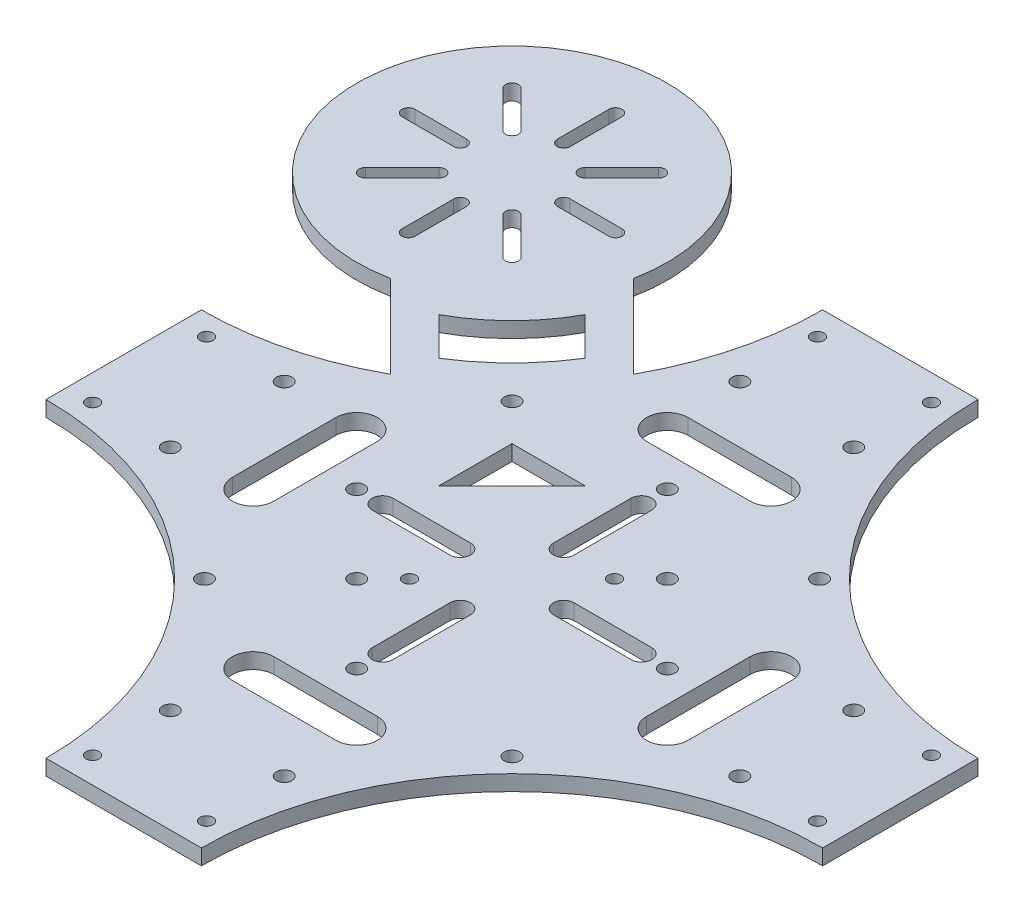
SolidWorks part; units mm, degrees
ref_plane "前视基准面" through (0, 0, 0) normal (0, 0, 1) x (1, 0, 0)
ref_plane "上视基准面" through (0, 0, 0) normal (0, 1, 0) x (1, 0, 0)
ref_plane "右视基准面" through (0, 0, 0) normal (1, 0, 0) x (0, 0, -1)
sketch "草图1" plane through (0, 0, 0) normal (0, 1, 0) x (1, 0, 0)
  line L0 (0, 0) -> (0, 75)
  line L1 (0, 0) -> (75, 0)
  line L2 (0, 0) -> (0, -75)
  line L3 (0, 0) -> (-75, 0)
  line L4 (0, 75) -> (15, 75)
  line L5 (0, 75) -> (-15, 75)
  line L6 (75, 0) -> (75, 15)
  line L7 (75, 0) -> (75, -15)
  line L8 (0, -75) -> (15, -75)
  line L9 (0, -75) -> (-15, -75)
  line L10 (-75, 0) -> (-75, -15)
  line L11 (-75, 0) -> (-75, 15)
  line L12 (75, 0) -> (70, 0)
  arc A0 (-75, 15) -> (-15, 75) centre (-75, 75) ccw
  arc A1 (15, 75) -> (75, 15) centre (75, 75) ccw
  arc A2 (75, -15) -> (15, -75) centre (75, -75) ccw
  arc A3 (-15, -75) -> (-75, -15) centre (-75, -75) ccw
  circle A4 centre (-11, 70) radius 1.25
  circle A5 centre (11, 70) radius 1.25
  circle A6 centre (70, -11) radius 1.25
  circle A7 centre (70, 11) radius 1.25
  circle A8 centre (-11, -70) radius 1.25
  circle A9 centre (11, -70) radius 1.25
  circle A10 centre (-70, 11) radius 1.25
  circle A11 centre (-70, -11) radius 1.25
  point P9 (0, 0)
  point P21 (0, 0)
  point P32 (0, 0)
  point P35 (0, 0)
  point P44 (0, 0)
  dimension "D1" = 4
extrude "凸台-拉伸1" add sketch "草图1" along normal blind 3 contours A2 L7 L1 L2 L8 A9 A6 | A3 L9 L2 L3 L10 A11 A8 | A0 L11 L3 L0 L5 A4 A10 | A1 L4 L0 L1 L6 A7 A5
sketch "草图2" plane through (0, 0, 0) normal (0, -1, 0) x (1, 0, 0)
  line L0 (0, 0) -> (-32.5736, -32.5736)
  line L1 (0, 0) -> (32.5736, -32.5736)
  line L2 (-31.4663, 0.3536) -> (-0.3536, 31.4663)
  line L3 (31.4663, -0.3536) -> (-0.3536, 31.4663)
  line L4 (0.3536, -31.4663) -> (31.4663, -0.3536)
  line L5 (0.3536, -31.4663) -> (-31.4663, 0.3536)
  arc A0 (-15, -75) -> (-75, -15) centre (-75, -75) ccw construction
  circle A2 centre (0.3536, -31.4663) radius 1.5
  circle A3 centre (31.4663, -0.3536) radius 1.5
  circle A4 centre (-0.3536, 31.4663) radius 1.5
  circle A5 centre (-31.4663, 0.3536) radius 1.5
  point P12 (-15.5563, -15.5563)
  point P16 (-15.9099, 15.9099)
  point P17 (15.9099, -15.9099)
extrude "切除-拉伸1" cut sketch "草图2" against normal blind 3 contours A3 | A2 | A5 | A4
sketch "草图3" plane through (0, 3, 0) normal (0, 1, 0) x (1, 0, 0)
  line L0 (0.3536, 31.4663) -> (-31.4663, -0.3536)
  line L1 (-15.5563, 15.5563) -> (-22.6274, 22.6274)
  line L2 (-15.5563, 15.5563) -> (-12.0208, 19.0919)
  line L3 (-15.5563, 15.5563) -> (-19.0919, 12.0208)
  line L4 (-19.0919, 12.0208) -> (-22.6274, 22.6274)
  line L5 (-12.0208, 19.0919) -> (-22.6274, 22.6274)
extrude "切除-拉伸2" cut sketch "草图3" against normal blind 3 contours L0 L5 L1 | L4 L0 L1
sketch "草图4" plane through (0, 3, 0) normal (0, 1, 0) x (1, 0, 0)
  line L0 (31.4663, 0.3536) -> (-0.3536, -31.4663)
  line L1 (0, 0) -> (21.2132, -21.2132)
  line L2 (28.2843, -14.1421) -> (14.1421, -28.2843)
  line L3 (14.1421, -28.2843) -> (28.2843, -14.1421) construction
  line L4 (8.4817, -22.6239) -> (22.6239, -8.4817)
  line L5 (19.8025, -33.9447) -> (33.9447, -19.8025)
  arc A0 (8.4817, -22.6239) -> (19.8025, -33.9447) centre (14.1421, -28.2843) ccw
  arc A1 (33.9447, -19.8025) -> (22.6239, -8.4817) centre (28.2843, -14.1421) ccw
  point P9 (21.2132, -21.2132)
extrude "切除-拉伸3" cut sketch "草图4" against normal blind 3
sketch "草图5" plane through (0, 3, 0) normal (0, 1, 0) x (1, 0, 0)
  line L0 (-12.0208, 19.0919) -> (-8.4853, 22.6274)
  line L1 (-8.4853, 22.6274) -> (-22.6274, 22.6274)
  line L2 (-19.0919, 12.0208) -> (-22.6274, 8.4853)
  line L3 (-22.6274, 8.4853) -> (-22.6274, 22.6274)
  line L4 (-12.0208, 19.0919) -> (-22.6274, 22.6274)
  line M28 (-19.0919, 12.0208) -> (-22.6274, 22.6274)
extrude "切除-拉伸4" cut sketch "草图5" against normal blind 10 contours L3 L2 M28 | L4 L0 L1
sketch "草图6" plane through (0, 3, 0) normal (0, 1, 0) x (1, 0, 0)
  line L0 (0, 0) -> (-28.2843, -28.2843)
  line L1 (-28.2843, -28.2843) -> (-35.3553, -21.2132)
  line L2 (0, 0) -> (-22.6274, 22.6274)
  circle A0 centre (-35.3553, -21.2132) radius 1.5
  circle A1 centre (-21.2132, -35.3553) radius 1.5
  circle A2 centre (35.3553, 21.2132) radius 1.5
  circle A3 centre (21.2132, 35.3553) radius 1.5
extrude "切除-拉伸5" cut sketch "草图6" against normal blind 10 contours A1 | A0 | A2 | A3
sketch "草图7" plane through (0, 3, 0) normal (0, 1, 0) x (1, 0, 0)
  circle A0 centre (-29.6985, 29.6985) radius 1.5
  circle A1 centre (29.6985, 29.6985) radius 1.5
  circle A2 centre (29.6985, -29.6985) radius 1.5
  circle A3 centre (-29.6985, -29.6985) radius 1.5
  point P11 (0, 0)
  dimension "D1" = 4
extrude "切除-拉伸8" cut sketch "草图7" against normal blind 10
sketch "草图8" plane through (0, 3, 0) normal (0, 1, 0) x (1, 0, 0)
  circle A0 centre (-11, 55) radius 1.5
  circle A1 centre (11, 55) radius 1.5
  circle A2 centre (55, 11) radius 1.5
  circle A3 centre (55, -11) radius 1.5
  circle A4 centre (11, -55) radius 1.5
  circle A5 centre (-11, -55) radius 1.5
  circle A6 centre (-55, -11) radius 1.5
  circle A7 centre (-55, 11) radius 1.5
  point P21 (0, 0)
  dimension "D1" = 4
extrude "切除-拉伸9" cut sketch "草图8" against normal blind 10
sketch "草图9" plane through (0, 3, 0) normal (0, 1, 0) x (1, 0, 0)
  circle A0 centre (0, 0) radius 15
extrude "切除-拉伸10" cut sketch "草图9" against normal blind 10
sketch "草图11" plane through (0, 3, 0) normal (0, 1, 0) x (1, 0, 0)
  circle A0 centre (-35.3553, -21.2132) radius 1.5
  circle A2 centre (35.3553, 21.2132) radius 1.5
  circle A3 centre (21.2132, 35.3553) radius 1.5
  circle A4 centre (0.3536, 31.4663) radius 1.5
  circle A5 centre (31.4663, 0.3536) radius 1.5
  circle A6 centre (-0.3536, -31.4663) radius 1.5
  circle A7 centre (-31.4663, -0.3536) radius 1.5
  circle A8 centre (-21.2132, -35.3553) radius 1.5
extrude "凸台-拉伸3" add sketch "草图11" against normal blind 3
sketch "草图12" plane through (0, 3, 0) normal (0, 1, 0) x (1, 0, 0)
  line L0 (0, 0) -> (-40, 0)
  line L1 (-40, 0) -> (-40, 10)
  line L2 (-40, 0) -> (-40, -10)
  line L3 (-40, -10) -> (-40, 10) construction
  line L4 (-44, -10) -> (-44, 10)
  line L5 (-36, -10) -> (-36, 10)
  line L6 (-10, 40) -> (10, 40) construction
  line L7 (-10, 44) -> (10, 44)
  line L8 (-10, 36) -> (10, 36)
  line L9 (40, 10) -> (40, -10) construction
  line L10 (44, 10) -> (44, -10)
  line L11 (36, 10) -> (36, -10)
  line L12 (10, -40) -> (-10, -40) construction
  line L13 (10, -44) -> (-10, -44)
  line L14 (10, -36) -> (-10, -36)
  arc A0 (-44, -10) -> (-36, -10) centre (-40, -10) ccw
  arc A1 (-36, 10) -> (-44, 10) centre (-40, 10) ccw
  arc A2 (-10, 44) -> (-10, 36) centre (-10, 40) ccw
  arc A3 (10, 36) -> (10, 44) centre (10, 40) ccw
  arc A4 (44, 10) -> (36, 10) centre (40, 10) ccw
  arc A5 (36, -10) -> (44, -10) centre (40, -10) ccw
  arc A6 (10, -44) -> (10, -36) centre (10, -40) ccw
  arc A7 (-10, -36) -> (-10, -44) centre (-10, -40) ccw
  point P3 (-40, 0)
  point P13 (0, 40)
  point P20 (40, 0)
  point P27 (0, -40)
  point P34 (0, 0)
  dimension "D1" = 4
extrude "切除-拉伸12" cut sketch "草图12" against normal blind 3
sketch "草图14" plane through (0, 3, 0) normal (0, 1, 0) x (1, 0, 0)
  line L0 (22.8277, -8.285) -> (8.285, -22.8277) construction
  line L1 (19.8025, -33.9447) -> (33.9447, -19.8025) construction
  line L2 (8.285, -22.8277) -> (22.8277, -8.285)
  line L3 (22.8277, -8.285) -> (19.8025, -33.9447)
  line L4 (19.8025, -33.9447) -> (33.9447, -19.8025)
  arc A0 (8.285, -22.8277) -> (19.8025, -33.9447) centre (14.1421, -28.2843) ccw
  arc A1 (8.285, -22.8277) -> (19.8025, -33.9447) centre (14.1421, -28.2843) ccw construction
  arc A2 (33.9447, -19.8025) -> (22.8277, -8.285) centre (28.2843, -14.1421) ccw construction
  arc A3 (22.8277, -8.285) -> (32.1857, -7.1522) centre (28.2843, -14.1421) ccw
  circle A4 centre (28.2843, -14.1421) radius 8.005
extrude "凸台-拉伸4" add sketch "草图14" against normal blind 3 contours A3 A4 L3 | L2 A3 L3 | A3 L2 A0 L3 | A3 L3 L4
sketch "草图15" plane through (0, 3, 0) normal (0, 1, 0) x (1, 0, 0)
  circle A0 centre (0, 0) radius 15
extrude "凸台-拉伸5" add sketch "草图15" against normal blind 3
sketch "草图17" plane through (0, 3, 0) normal (0, 1, 0) x (1, 0, 0)
  line L0 (0, 0) -> (0, -20)
  line L1 (0, -20) -> (0, -10) construction
  line L2 (-2, -20) -> (-2, -10)
  line L3 (2, -20) -> (2, -10)
  line L4 (-20, 0) -> (-10, 0) construction
  line L5 (-20, 2) -> (-10, 2)
  line L6 (-20, -2) -> (-10, -2)
  line L7 (0, 20) -> (0, 10) construction
  line L8 (2, 20) -> (2, 10)
  line L9 (-2, 20) -> (-2, 10)
  line L10 (20, 0) -> (10, 0) construction
  line L11 (20, -2) -> (10, -2)
  line L12 (20, 2) -> (10, 2)
  arc A0 (-2, -20) -> (2, -20) centre (0, -20) ccw
  arc A1 (2, -10) -> (-2, -10) centre (0, -10) ccw
  arc A2 (-20, 2) -> (-20, -2) centre (-20, 0) ccw
  arc A3 (-10, -2) -> (-10, 2) centre (-10, 0) ccw
  arc A4 (2, 20) -> (-2, 20) centre (0, 20) ccw
  arc A5 (-2, 10) -> (2, 10) centre (0, 10) ccw
  arc A6 (20, -2) -> (20, 2) centre (20, 0) ccw
  arc A7 (10, 2) -> (10, -2) centre (10, 0) ccw
  point P3 (0, -15)
  point P13 (-15, 0)
  point P20 (0, 15)
  point P27 (15, 0)
  point P33 (0, 0)
  dimension "D1" = 4
extrude "切除-拉伸13" cut sketch "草图17" against normal blind 3 contours L8 A5 L9 A4 | L12 A7 L11 A6 | L3 A1 L2 A0 | L5 A3 L6 A2
sketch "草图18" plane through (0, 3, 0) normal (0, 1, 0) x (1, 0, 0)
  line L0 (0, 0) -> (-32.5736, 32.5736)
  line L1 (-32.5736, 32.5736) -> (-46.7157, 46.7157)
  line L2 (-50.2513, 50.2513) -> (-61.9773, 38.5252)
  line L3 (-46.7157, 46.7157) -> (-50.2513, 50.2513)
  line L4 (-61.9773, 38.5252) -> (-38.5252, 61.9773)
  line L5 (-38.5252, 61.9773) -> (-22.5002, 45.9523)
  line L6 (-61.9773, 38.5252) -> (-45.9523, 22.5002)
  arc A0 (-75, 15) -> (-15, 75) centre (-75, 75) ccw construction
  circle A1 centre (-67.9289, 67.9289) radius 30
  circle A2 centre (-75, 75) radius 60
extrude "凸台-拉伸7" add sketch "草图18" against normal blind 3 contours L4 A1 L2 | L2 A1 L3 | L3 A1 L4 | L6 A2 L1 A1 | L1 A2 L5 A1
sketch "草图19" plane through (0, 3, 0) normal (0, 1, 0) x (1, 0, 0)
  line L0 (-61.9773, 38.5252) -> (-38.5252, 61.9773)
  line L1 (-50.2513, 50.2513) -> (-36.1091, 36.1091)
  line L2 (-36.1091, 36.1091) -> (-43.1802, 29.0381)
  line L3 (-36.1091, 36.1091) -> (-29.0381, 43.1802)
  line L4 (-29.0381, 43.1802) -> (-37.1408, 51.2829)
  line L5 (-37.1408, 51.2829) -> (-51.2829, 37.1408)
  line L6 (-51.2829, 37.1408) -> (-43.1802, 29.0381)
  circle A1 centre (-67.9289, 67.9289) radius 35
  circle A2 centre (-67.9289, 67.9289) radius 45
extrude "切除-拉伸14" cut sketch "草图19" against normal blind 3 contours L1 A2 L4 A1 | L6 A2 L1 A1
sketch "草图21" plane through (0, 3, 0) normal (0, 1, 0) x (1, 0, 0)
  line L0 (-61.9773, 38.5252) -> (-38.5252, 61.9773)
  line L1 (-67.9289, 67.9289) -> (-53.7868, 53.7868)
  line L2 (-82.0711, 82.0711) -> (-75, 75)
  line L3 (-67.9289, 67.9289) -> (-82.0711, 82.0711)
  line L4 (-53.7868, 53.7868) -> (-60.8579, 60.8579)
  line L5 (-82.0711, 82.0711) -> (-75, 75) construction
  line L6 (-81.1872, 82.955) -> (-74.1161, 75.8839)
  line L7 (-82.955, 81.1872) -> (-75.8839, 74.1161)
  line L8 (-60.8579, 60.8579) -> (-53.7868, 53.7868) construction
  line L9 (-59.974, 61.7417) -> (-52.9029, 54.6707)
  line L10 (-61.7417, 59.974) -> (-54.6707, 52.9029)
  arc A0 (-81.1872, 82.955) -> (-82.955, 81.1872) centre (-82.0711, 82.0711) ccw
  arc A1 (-75.8839, 74.1161) -> (-74.1161, 75.8839) centre (-75, 75) ccw
  arc A2 (-59.974, 61.7417) -> (-61.7417, 59.974) centre (-60.8579, 60.8579) ccw
  arc A3 (-54.6707, 52.9029) -> (-52.9029, 54.6707) centre (-53.7868, 53.7868) ccw
  point P2 (-78.5355, 78.5355)
  point P15 (-57.3223, 57.3223)
extrude "切除-拉伸15" cut sketch "草图21" against normal blind 3
pattern_circular "阵列(圆周)1" count 8 over 360 about axis through (-67.9289, 0, -67.9289) along (0, 1, 0) of "切除-拉伸15"
sketch "草图22" plane through (0, 3, 0) normal (0, 1, 0) x (1, 0, 0)
  line L0 (0, 0) -> (9.8995, 9.8995)
  line L1 (0, 0) -> (-9.8995, -9.8995)
  circle A0 centre (9.8995, 9.8995) radius 1.25
  circle A1 centre (-9.8995, -9.8995) radius 1.25
extrude "切除-拉伸17" cut sketch "草图22" against normal blind 3 contours A0 | A1
sketch "草图23" plane through (0, 3, 0) normal (0, 1, 0) x (1, 0, 0)
  circle A0 centre (0, 30) radius 1.5
  circle A1 centre (30, 0) radius 1.5
  circle A2 centre (0, -30) radius 1.5
  circle A3 centre (-30, 0) radius 1.5
  point P13 (0, 0)
  dimension "D1" = 4
extrude "切除-拉伸18" cut sketch "草图23" against normal blind 10
sketch "草图24" plane through (0, 3, 0) normal (0, 1, 0) x (1, 0, 0)
  circle A0 centre (-15, -15) radius 1.5
  circle A1 centre (15, 15) radius 1.5
extrude "切除-拉伸19" cut sketch "草图24" against normal blind 10
sketch "草图25" plane through (0, 3, 0) normal (0, 1, 0) x (1, 0, 0)
  line L0 (0, 10) -> (0, 25)
  line L1 (0, 10) -> (0, 25) construction
  line L2 (-2, 10) -> (-2, 25)
  line L3 (2, 10) -> (2, 25)
  line L4 (10, 0) -> (25, 0) construction
  line L5 (10, 2) -> (25, 2)
  line L6 (10, -2) -> (25, -2)
  line L7 (0, -10) -> (0, -25) construction
  line L8 (2, -10) -> (2, -25)
  line L9 (-2, -10) -> (-2, -25)
  line L10 (-10, 0) -> (-25, 0) construction
  line L11 (-10, -2) -> (-25, -2)
  line L12 (-10, 2) -> (-25, 2)
  arc A0 (-2, 10) -> (2, 10) centre (0, 10) ccw
  arc A1 (2, 25) -> (-2, 25) centre (0, 25) ccw
  arc A3 (10, 2) -> (10, -2) centre (10, 0) ccw
  arc A4 (25, -2) -> (25, 2) centre (25, 0) ccw
  arc A5 (2, -10) -> (-2, -10) centre (0, -10) ccw
  arc A6 (-2, -25) -> (2, -25) centre (0, -25) ccw
  arc A7 (-10, -2) -> (-10, 2) centre (-10, 0) ccw
  arc A8 (-25, 2) -> (-25, -2) centre (-25, 0) ccw
  point P4 (0, 17.5)
  point P14 (17.5, 0)
  point P21 (0, -17.5)
  point P28 (-17.5, 0)
  point P33 (0, 0)
  dimension "D1" = 4
extrude "切除-拉伸20" cut sketch "草图25" against normal blind 10 contours L12 A8 L11 A7 | L5 A4 L6 A3 | A1 L2 A0 L3 | L8 A6 L9 A5
